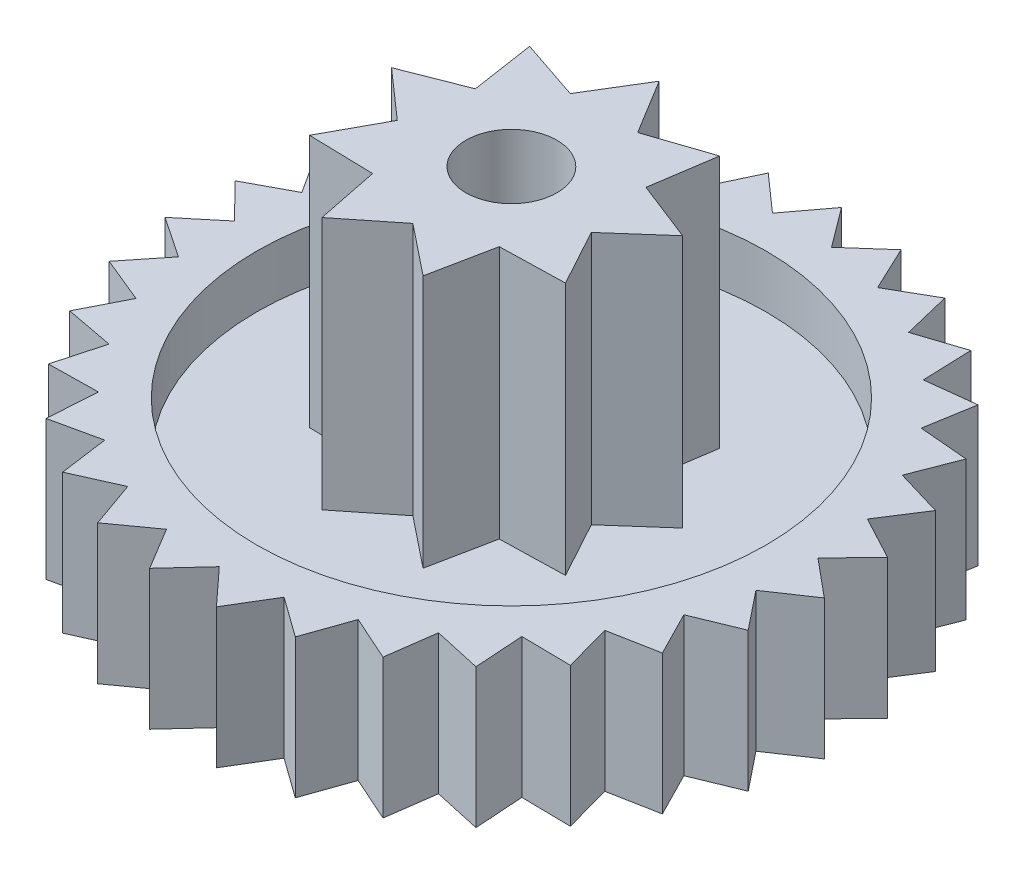
SolidWorks part; units mm, degrees
ref_plane "Front Plane" through (0, 0, 0) normal (0, 0, 1) x (1, 0, 0)
ref_plane "Top Plane" through (0, 0, 0) normal (0, 1, 0) x (1, 0, 0)
ref_plane "Right Plane" through (0, 0, 0) normal (1, 0, 0) x (0, 0, -1)
sketch "Sketch1" plane through (0, 0, 0) normal (0, 0, 1) x (1, 0, 0)
  line L0 (0, 7.3) -> (0, 0)
  line L1 (0, -55) -> (0, 55) construction
  line L2 (0, 0) -> (1.97, 0)
  line L4 (6.7, 0.4) -> (6.7, 3.23)
  line L5 (6.7, 3.23) -> (5.17, 3.23)
  line L6 (3, 2.16) -> (3, 7.3)
  line L7 (3, 7.3) -> (0, 7.3)
  line L8 (5.17, 3.23) -> (5.17, 2.16)
  line L9 (5.17, 2.16) -> (3, 2.16)
  line L10 (5.17, 0.4) -> (6.7, 0.4)
  line L11 (1.97, 0.9) -> (5.17, 0.9)
  line L12 (1.97, 0.9) -> (1.97, 0)
  line L14 (5.17, 0.9) -> (5.17, 0.4)
  dimension "D1" = 3
  dimension "D2" = 6.7
  dimension "D3" = 7.3
  dimension "D4" = 2.83
  dimension "D5" = 5.17
  dimension "D6" = 0.5
  dimension "D7" = 0.9
  dimension "D8" = 5.14
  dimension "D9" = 1.97
revolve "Revolve1" add sketch "Sketch1" angle 360 about L0
sketch "Sketch3" plane through (0, 3.23, 0) normal (0, 1, 0) x (1, 0, 0)
  line L0 (0, 6.7) -> (-0.5999, 5.8996)
  line L1 (-0.5999, 5.8996) -> (0, 0) construction
  line L2 (0, 0) -> (0.5999, 5.8996) construction
  line L3 (0.5999, 5.8996) -> (0, 6.7)
  line L4 (0, -55) -> (0, 55) construction
  line L5 (1.3487, 6.5629) -> (0.5999, 5.8996)
  line L6 (1.7752, 5.658) -> (1.3487, 6.5629)
  line L7 (2.6422, 6.157) -> (1.7752, 5.658)
  line L8 (2.8778, 5.1849) -> (2.6422, 6.157)
  line L9 (3.8275, 5.4991) -> (2.8778, 5.1849)
  line L10 (3.8626, 4.4994) -> (3.8275, 5.4991)
  line L11 (4.8561, 4.6161) -> (3.8626, 4.4994)
  line L12 (4.6893, 3.6298) -> (4.8561, 4.6161)
  line L13 (5.6859, 3.5441) -> (4.6893, 3.6298)
  line L14 (5.324, 2.6115) -> (5.6859, 3.5441)
  line L15 (6.2829, 2.3269) -> (5.324, 2.6115)
  line L16 (5.7407, 1.4864) -> (6.2829, 2.3269)
  line L17 (6.6227, 1.0146) -> (5.7407, 1.4864)
  line L18 (5.9224, 0.3003) -> (6.6227, 1.0146)
  line L19 (6.6914, -0.3393) -> (5.9224, 0.3003)
  line L20 (5.8616, -0.898) -> (6.6914, -0.3393)
  line L21 (6.4861, -1.6794) -> (5.8616, -0.898)
  line L22 (5.5609, -2.0595) -> (6.4861, -1.6794)
  line L23 (6.0153, -2.9506) -> (5.5609, -2.0595)
  line L24 (5.0325, -3.1368) -> (6.0153, -2.9506)
  line L25 (5.2982, -4.1011) -> (5.0325, -3.1368)
  line L26 (4.298, -4.0856) -> (5.2982, -4.1011)
  line L27 (4.3642, -5.0837) -> (4.298, -4.0856)
  line L28 (3.3876, -4.8671) -> (4.3642, -5.0837)
  line L29 (3.2515, -5.8581) -> (3.3876, -4.8671)
  line L30 (2.3385, -5.4494) -> (3.2515, -5.8581)
  line L31 (2.0057, -6.3927) -> (2.3385, -5.4494)
  line L32 (1.1937, -5.8086) -> (2.0057, -6.3927)
  line L33 (0.6778, -6.6656) -> (1.1937, -5.8086)
  line L34 (0, -5.93) -> (0.6778, -6.6656)
  line L35 (-0.6778, -6.6656) -> (0, -5.93)
  line L36 (-1.1937, -5.8086) -> (-0.6778, -6.6656)
  line L37 (-2.0057, -6.3927) -> (-1.1937, -5.8086)
  line L38 (-2.3385, -5.4494) -> (-2.0057, -6.3927)
  line L39 (-3.2515, -5.8581) -> (-2.3385, -5.4494)
  line L40 (-3.3876, -4.8671) -> (-3.2515, -5.8581)
  line L41 (-4.3642, -5.0837) -> (-3.3876, -4.8671)
  line L42 (-4.298, -4.0856) -> (-4.3642, -5.0837)
  line L43 (-5.2982, -4.1011) -> (-4.298, -4.0856)
  line L44 (-5.0325, -3.1368) -> (-5.2982, -4.1011)
  line L45 (-6.0153, -2.9506) -> (-5.0325, -3.1368)
  line L46 (-5.5609, -2.0595) -> (-6.0153, -2.9506)
  line L47 (-6.4861, -1.6794) -> (-5.5609, -2.0595)
  line L48 (-5.8616, -0.898) -> (-6.4861, -1.6794)
  line L49 (-6.6914, -0.3393) -> (-5.8616, -0.898)
  line L50 (-5.9224, 0.3003) -> (-6.6914, -0.3393)
  line L51 (-6.6227, 1.0146) -> (-5.9224, 0.3003)
  line L52 (-5.7407, 1.4864) -> (-6.6227, 1.0146)
  line L53 (-6.2829, 2.3269) -> (-5.7407, 1.4864)
  line L54 (-5.324, 2.6115) -> (-6.2829, 2.3269)
  line L55 (-5.6859, 3.5441) -> (-5.324, 2.6115)
  line L56 (-4.6893, 3.6298) -> (-5.6859, 3.5441)
  line L57 (-4.8561, 4.6161) -> (-4.6893, 3.6298)
  line L58 (-3.8626, 4.4994) -> (-4.8561, 4.6161)
  line L59 (-3.8275, 5.4991) -> (-3.8626, 4.4994)
  line L60 (-2.8778, 5.1849) -> (-3.8275, 5.4991)
  line L61 (-2.6422, 6.157) -> (-2.8778, 5.1849)
  line L62 (-1.7752, 5.658) -> (-2.6422, 6.157)
  line L63 (-1.3487, 6.5629) -> (-1.7752, 5.658)
  line L64 (-0.5999, 5.8996) -> (-1.3487, 6.5629)
  circle A0 centre (0, 0) radius 5.93 construction
  circle A1 centre (0, 0) radius 6.7 construction
  circle A4 centre (0, 0) radius 7.2
  circle A5 centre (0, 0) radius 7.2
  point P106 (0, 0)
  dimension "D2" = 11.86
  dimension "D1" = 11.613
  dimension "D3" = 0.5
  dimension "D4" = 31
extrude "Cut-Extrude1" cut sketch "Sketch3" against normal through all
sketch "Sketch4" plane through (0, 7.3, 0) normal (0, 1, 0) x (1, 0, 0)
  line L0 (0, 3) -> (-0.684, 1.8794)
  line L1 (0, -55) -> (0, 55) construction
  line L2 (-0.684, 1.8794) -> (0, 0) construction
  line L3 (0, 0) -> (0.684, 1.8794) construction
  line L4 (0.684, 1.8794) -> (0, 3)
  line L5 (1.9284, 2.2981) -> (0.684, 1.8794)
  line L6 (1.7321, 1) -> (1.9284, 2.2981)
  line L7 (2.9544, 0.5209) -> (1.7321, 1)
  line L8 (1.9696, -0.3473) -> (2.9544, 0.5209)
  line L9 (2.5981, -1.5) -> (1.9696, -0.3473)
  line L10 (1.2856, -1.5321) -> (2.5981, -1.5)
  line L11 (1.0261, -2.8191) -> (1.2856, -1.5321)
  line L12 (0, -2) -> (1.0261, -2.8191)
  line L13 (-1.0261, -2.8191) -> (0, -2)
  line L14 (-1.2856, -1.5321) -> (-1.0261, -2.8191)
  line L15 (-2.5981, -1.5) -> (-1.2856, -1.5321)
  line L16 (-1.9696, -0.3473) -> (-2.5981, -1.5)
  line L17 (-2.9544, 0.5209) -> (-1.9696, -0.3473)
  line L18 (-1.7321, 1) -> (-2.9544, 0.5209)
  line L19 (-1.9284, 2.2981) -> (-1.7321, 1)
  line L20 (-0.684, 1.8794) -> (-1.9284, 2.2981)
  circle A0 centre (0, 0) radius 2 construction
  circle A1 centre (0, 0) radius 3 construction
  circle A4 centre (0, 0) radius 3.5
  circle A5 centre (0, 0) radius 3.5
  point P40 (0, 0)
  dimension "D3" = 4
  dimension "D1" = 40
  dimension "D2" = 0.5
  dimension "D4" = 9
extrude "Cut-Extrude2" cut sketch "Sketch4" against normal up to surface (5.14 mm away) up to face at (0, 2.16, 3)
sketch "Sketch5" plane through (0, 7.3, 0) normal (0, 1, 0) x (1, 0, 0)
  circle A0 centre (0, 0) radius 0.925
  dimension "D1" = 1.85
extrude "Cut-Extrude3" cut sketch "Sketch5" against normal through all
